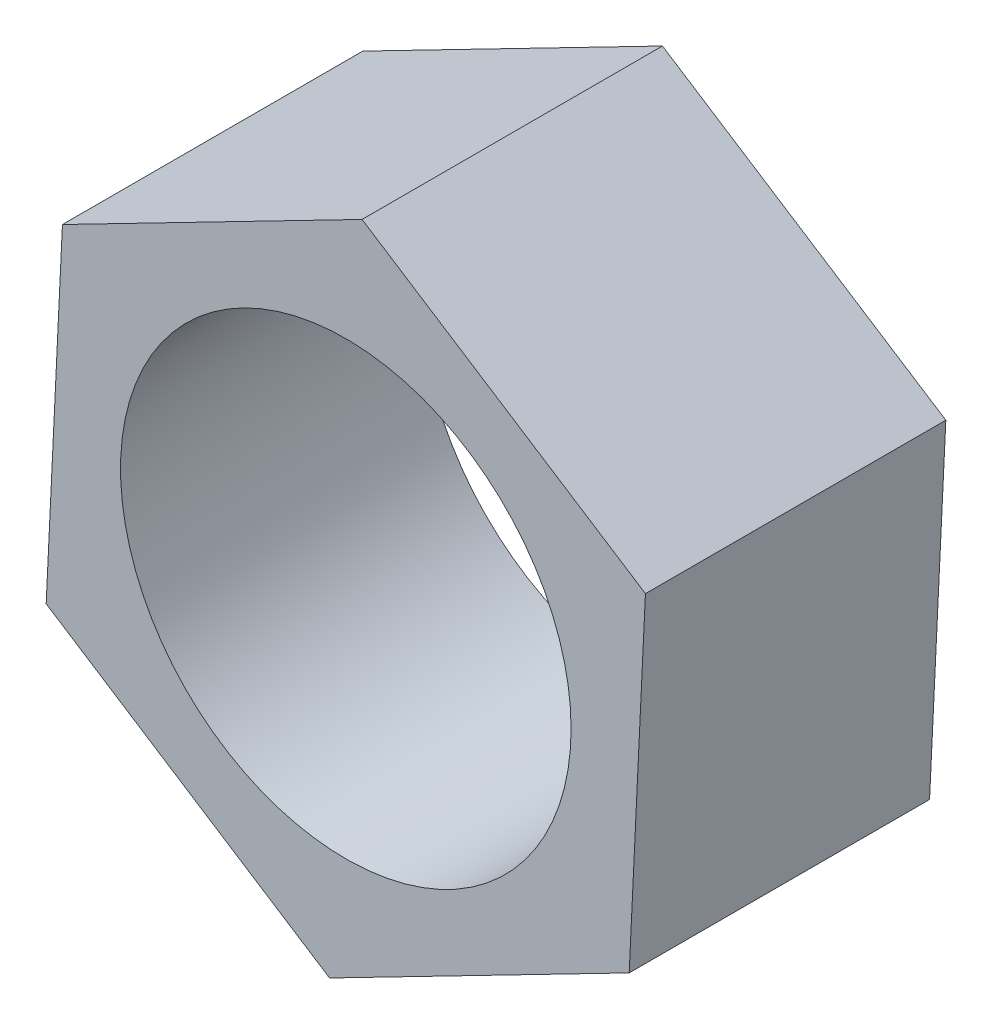
SolidWorks part; units mm, degrees
ref_plane "Front Plane" through (0, 0, 0) normal (0, 0, 1) x (1, 0, 0)
ref_plane "Top Plane" through (0, 0, 0) normal (0, 1, 0) x (1, 0, 0)
ref_plane "Right Plane" through (0, 0, 0) normal (1, 0, 0) x (0, 0, -1)
sketch "Sketch1" plane through (0, 0, 0) normal (0, 0, 1) x (1, 0, 0)
  line L1 (0.2165, 4.4823) -> (-3.7735, 2.4286)
  line L2 (-3.7735, 2.4286) -> (-3.99, -2.0537)
  line L3 (-3.99, -2.0537) -> (-0.2165, -4.4823)
  line L4 (-0.2165, -4.4823) -> (3.7735, -2.4286)
  line L5 (3.7735, -2.4286) -> (3.99, 2.0537)
  line L6 (3.99, 2.0537) -> (0.2165, 4.4823)
  circle A0 centre (0, 0) radius 3
  circle A1 centre (0, 0) radius 3.8863 construction
  dimension "D1" = 6
extrude "Boss-Extrude1" add sketch "Sketch1" along normal blind 4
